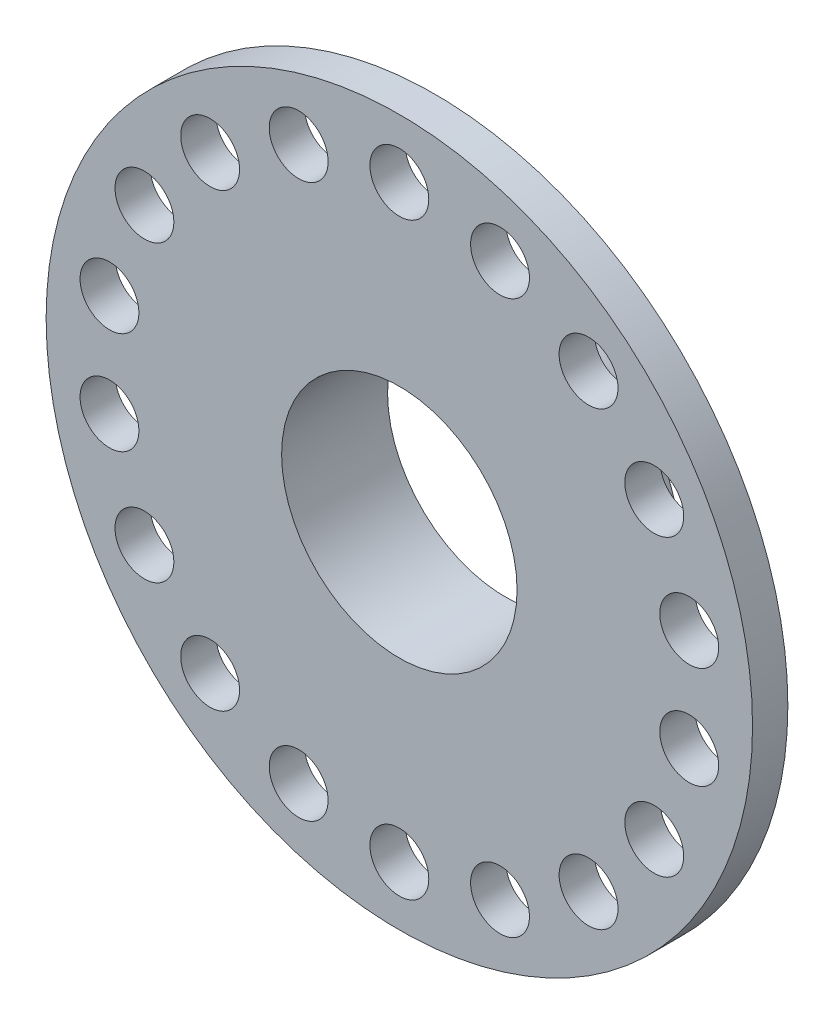
SolidWorks part; units mm, degrees
ref_plane "Front Plane" through (0, 0, 0) normal (0, 0, 1) x (1, 0, 0)
ref_plane "Top Plane" through (0, 0, 0) normal (0, 1, 0) x (1, 0, 0)
ref_plane "Right Plane" through (0, 0, 0) normal (1, 0, 0) x (0, 0, -1)
sketch "Sketch1" plane through (0, 0, 0) normal (0, 0, 1) x (1, 0, 0)
  circle A0 centre (0, 0) radius 15
  dimension "D1" = 30
extrude "Boss-Extrude1" add sketch "Sketch1" along normal blind 6
sketch "Sketch2" plane through (0, 0, 6) normal (0, 0, 1) x (1, 0, 0)
  circle A0 centre (0, 0) radius 30
  dimension "D1" = 60
extrude "Boss-Extrude2" add sketch "Sketch2" along normal blind 3
sketch "Sketch3" plane through (0, 0, 0) normal (0, 0, -1) x (-1, 0, 0)
  circle A0 centre (0, 0) radius 30
  circle A1 centre (0, 0) radius 15 construction
  dimension "D1" = 15
sketch "Sketch5" plane through (0, 0, 0) normal (0, 0, -1) x (-1, 0, 0)
  circle A0 centre (0, 0) radius 10
  dimension "D1" = 20
extrude "Cut-Extrude2" cut sketch "Sketch5" against normal through all
sketch "Sketch8" plane through (0, 0, 9) normal (0, 0, 1) x (1, 0, 0)
  circle A0 centre (0, 25) radius 2.5
  circle A1 centre (8.5505, 23.4923) radius 2.5
  circle A2 centre (16.0697, 19.1511) radius 2.5
  circle A3 centre (21.6506, 12.5) radius 2.5
  circle A4 centre (24.6202, 4.3412) radius 2.5
  circle A5 centre (24.6202, -4.3412) radius 2.5
  circle A6 centre (21.6506, -12.5) radius 2.5
  circle A7 centre (16.0697, -19.1511) radius 2.5
  circle A8 centre (8.5505, -23.4923) radius 2.5
  circle A9 centre (0, -25) radius 2.5
  circle A10 centre (-8.5505, -23.4923) radius 2.5
  circle A11 centre (-16.0697, -19.1511) radius 2.5
  circle A12 centre (-21.6506, -12.5) radius 2.5
  circle A13 centre (-24.6202, -4.3412) radius 2.5
  circle A14 centre (-24.6202, 4.3412) radius 2.5
  circle A15 centre (-21.6506, 12.5) radius 2.5
  circle A16 centre (-16.0697, 19.1511) radius 2.5
  circle A17 centre (-8.5505, 23.4923) radius 2.5
  point P40 (0, 0)
  dimension "D1" = 5
  dimension "D2" = 25
  dimension "D3" = 18
extrude "Cut-Extrude3" cut sketch "Sketch8" against normal through all
